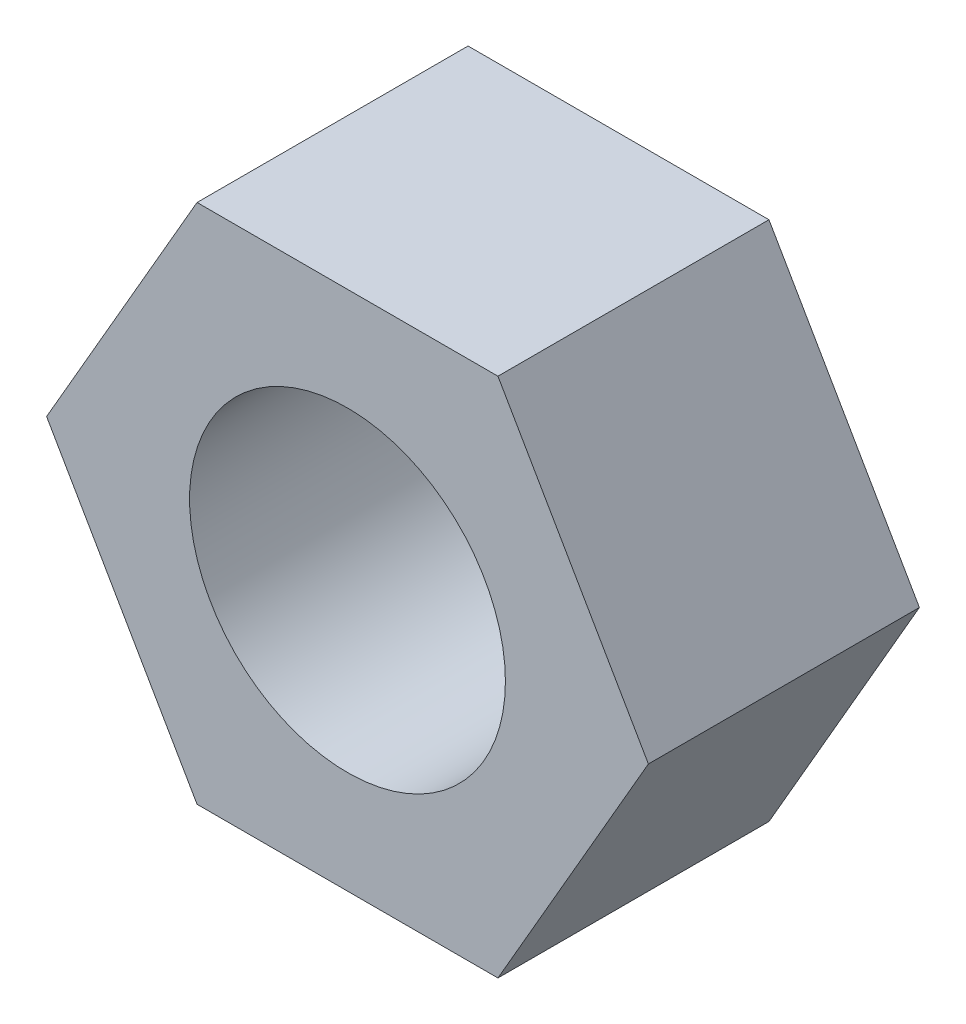
SolidWorks part; units mm, degrees
ref_plane "Front Plane" through (0, 0, 0) normal (0, 0, 1) x (1, 0, 0)
ref_plane "Top Plane" through (0, 0, 0) normal (0, 1, 0) x (1, 0, 0)
ref_plane "Right Plane" through (0, 0, 0) normal (1, 0, 0) x (0, 0, -1)
sketch "S01 - ISO 4032 M6 x 1 RH hex nut AF10 x 5.2" plane through (0, 0, 0) normal (0, 0, 1) x (1, 0, 0)
  line L0 (5.7735, 0) -> (2.8868, 5)
  line L1 (2.8868, 5) -> (-2.8868, 5)
  line L2 (-2.8868, 5) -> (-5.7735, 0)
  line L3 (-5.7735, 0) -> (-2.8868, -5)
  line L4 (-2.8868, -5) -> (2.8868, -5)
  line L5 (2.8868, -5) -> (5.7735, 0)
  circle A0 centre (0, 0) radius 3.03
  dimension "D1" = 6.06
  dimension "D2" = 2.8868
  dimension "D3" = 5.7735
  dimension "D4" = 2.8868
  dimension "D5" = 5.7735
  dimension "D6" = 5
  dimension "D7" = 5
extrude "01 - ISO 4032 M6 x 1 RH hex nut AF10 x 5.2" add sketch "S01 - ISO 4032 M6 x 1 RH hex nut AF10 x 5.2" along normal blind 5.2
